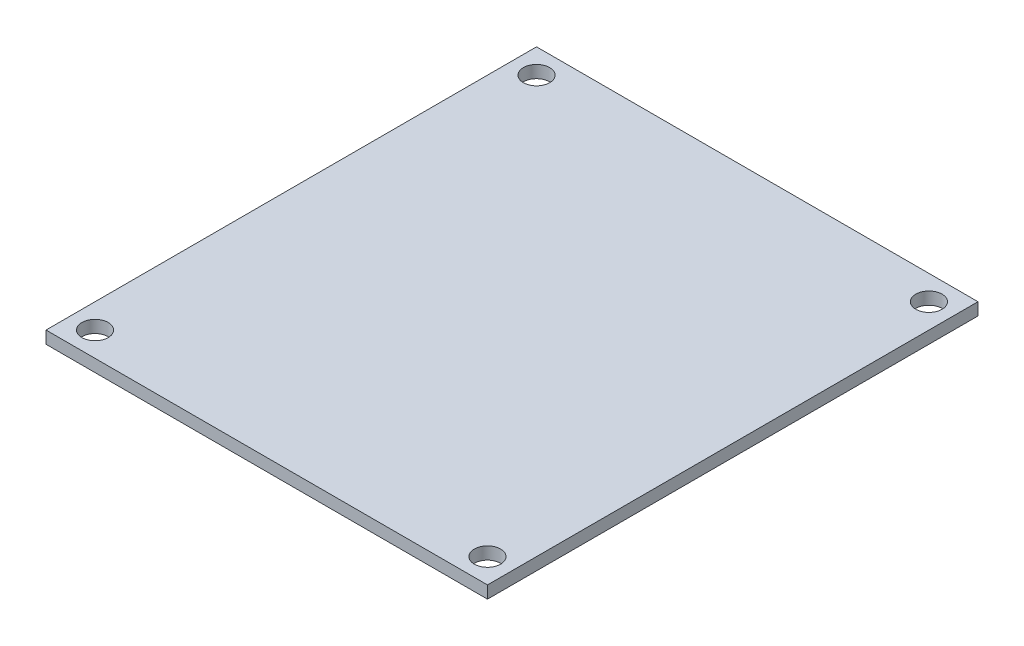
SolidWorks part; units mm, degrees
ref_plane "Front" through (0, 0, 0) normal (0, 0, 1) x (1, 0, 0)
ref_plane "Top" through (0, 0, 0) normal (0, 1, 0) x (1, 0, 0)
ref_plane "Right" through (0, 0, 0) normal (1, 0, 0) x (0, 0, -1)
sketch "Sketch1" plane through (0, 0, 0) normal (0, 1, 0) x (1, 0, 0)
  line L1 (-28.575, -31.75) -> (28.575, -31.75)
  line L2 (-28.575, -31.75) -> (-28.575, 31.75)
  line L3 (-28.575, 31.75) -> (28.575, 31.75)
  line L4 (28.575, -31.75) -> (28.575, 31.75)
  line L5 (-28.575, -31.75) -> (28.575, 31.75) construction
  line L6 (-28.575, 31.75) -> (28.575, -31.75) construction
  point P0 (0, 0)
  dimension "D1" = 57.15
  dimension "D2" = 63.5
extrude "Boss-Extrude1" add sketch "Sketch1" along normal blind 1.6
hole_wizard "M3 Clearance Hole1" positions "Sketch2" profile "Sketch3" hole size "M3" standard "ANSI Metric"
sketch "Sketch2" plane through (0, 1.6, 0) normal (0, 1, 0) x (1, 0, 0)
  line L0 (-25.4, 28.575) -> (-25.4, -28.575) construction
  line L1 (-25.4, -28.575) -> (25.4, -28.575) construction
  line L2 (25.4, -28.575) -> (25.4, 28.575) construction
  line L3 (25.4, 28.575) -> (-25.4, 28.575) construction
  line L5 (28.575, 31.75) -> (-28.575, 31.75) construction
  line L6 (28.575, -31.75) -> (28.575, 31.75) construction
  line L7 (-28.575, -31.75) -> (28.575, -31.75) construction
  line L8 (-28.575, 31.75) -> (-28.575, -31.75) construction
  point P0 (-25.4, 28.575)
  point P2 (25.4, 28.575)
  point P4 (25.4, -28.575)
  point P6 (-25.4, -28.575)
  dimension "D1" = 3.175
  dimension "D2" = 3.175
  dimension "D3" = 3.175
  dimension "D4" = 3.175
sketch "Sketch3" plane through (-25.4, 1.6, -28.575) normal (1, 0, 0) x (0, 0, 1)
  line L0 (0, 0) -> (0, 51.0215)
  line L1 (0, 51.0215) -> (1.7, 50)
  line L2 (1.7, 50) -> (1.7, 0)
  line L5 (1.7, 0) -> (0, 0)
  line L10 (0, 51.0215) -> (-1.7, 50) construction
  line L11 (0, -6.35) -> (0, 107.95) construction
  dimension "Hole Dia." = 3.4
  dimension "Hole Depth" = 50
  dimension "Drill Angle" = 118
